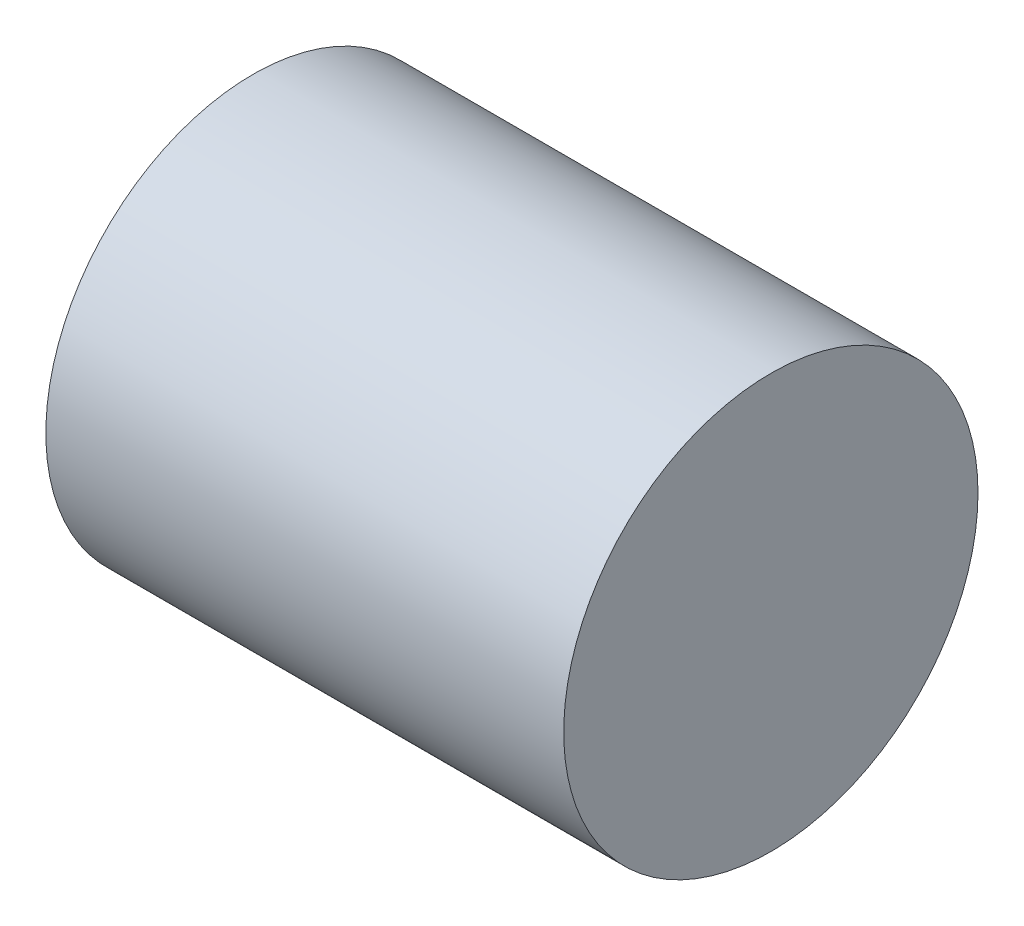
SolidWorks part; units mm, degrees
material "Messing"
ref_plane "Ebene vorne" through (0, 0, 0) normal (1, 0, 0) x (0, 1, 0)
ref_plane "Ebene oben" through (0, 0, 0) normal (0, 0, 1) x (0, 1, 0)
ref_plane "Ebene rechts" through (0, 0, 0) normal (0, 1, 0) x (-1, 0, 0)
sketch "Skizze1" plane through (0, 0, 0) normal (1, 0, 0) x (0, 1, 0)
  circle A0 centre (0, 0) radius 2
  dimension "D1" = 4
extrude "Aufsatz-Linear austragen1" add sketch "Skizze1" along normal blind 5
sketch "Skizze2" plane through (0, 0, 0) normal (-1, 0, 0) x (0, -1, 0)
  circle A0 centre (0, 0) radius 1.5
extrude "Schnitt-Linear austragen1" cut sketch "Skizze2" against normal blind 4
